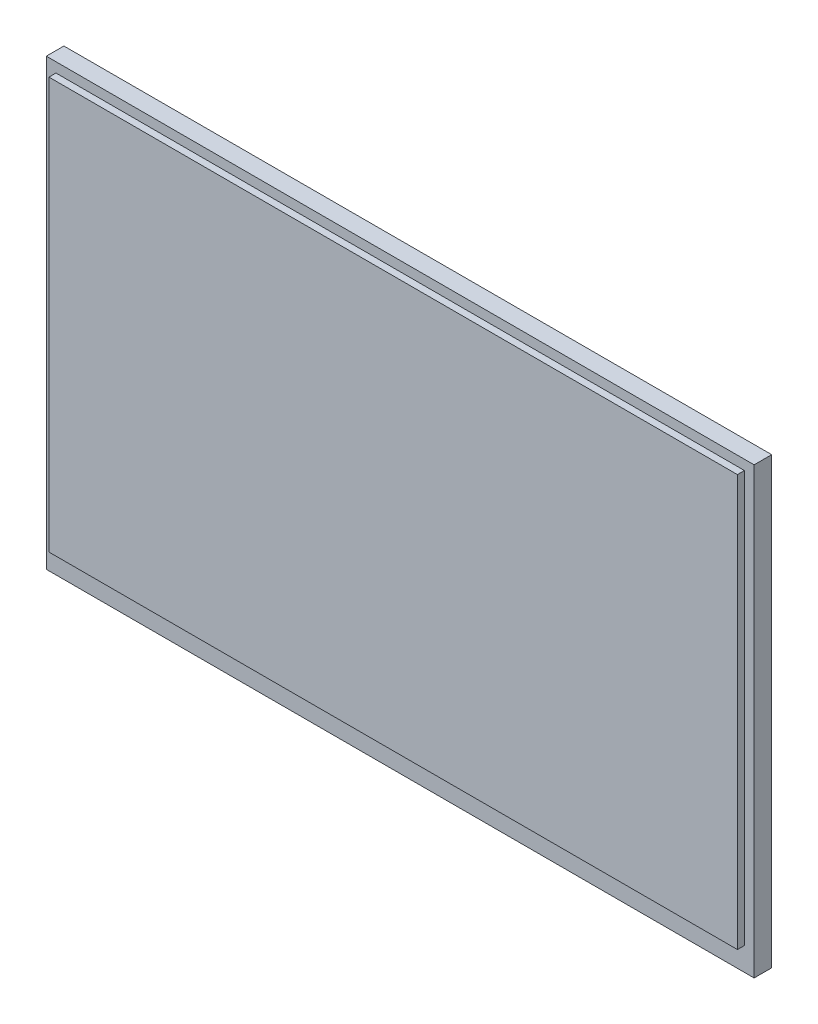
SolidWorks part; units mm, degrees
ref_plane "Front Plane" through (0, 0, 0) normal (0, 0, 1) x (1, 0, 0)
ref_plane "Top Plane" through (0, 0, 0) normal (0, 1, 0) x (1, 0, 0)
ref_plane "Right Plane" through (0, 0, 0) normal (1, 0, 0) x (0, 0, -1)
sketch "Sketch1" plane through (0, 0, 0) normal (0, 0, 1) x (1, 0, 0)
  line L1 (-60.4, 37.925) -> (60.4, 37.925)
  line L2 (-60.4, 37.925) -> (-60.4, -37.925)
  line L3 (-60.4, -37.925) -> (60.4, -37.925)
  line L4 (60.4, 37.925) -> (60.4, -37.925)
  line L5 (-60.4, 37.925) -> (60.4, -37.925) construction
  line L6 (-60.4, -37.925) -> (60.4, 37.925) construction
  point P0 (0, 0)
  dimension "D1" = 75.85
  dimension "D2" = 120.8
extrude "Boss-Extrude1" add sketch "Sketch1" along normal blind 3
sketch "Sketch2" plane through (0, 0, 3) normal (0, 0, 1) x (1, 0, 0)
  line L0 (60.4, 37.925) -> (-60.4, 37.925) construction
  line L1 (58.75, 36.255) -> (-58.75, 36.255)
  line L2 (58.75, 36.255) -> (58.75, -33.945)
  line L3 (58.75, -33.945) -> (-58.75, -33.945)
  line L4 (-58.75, 36.255) -> (-58.75, -33.945)
  line L5 (58.75, 36.255) -> (-58.75, -33.945) construction
  line L6 (58.75, -33.945) -> (-58.75, 36.255) construction
  point P0 (0, 1.155)
  point P5 (0, -2.6094)
  point P8 (0, 0)
  dimension "D1" = 70.2
  dimension "D2" = 117.5
  dimension "D3" = 1.67
extrude "Boss-Extrude2" add sketch "Sketch2" along normal blind 1.2
